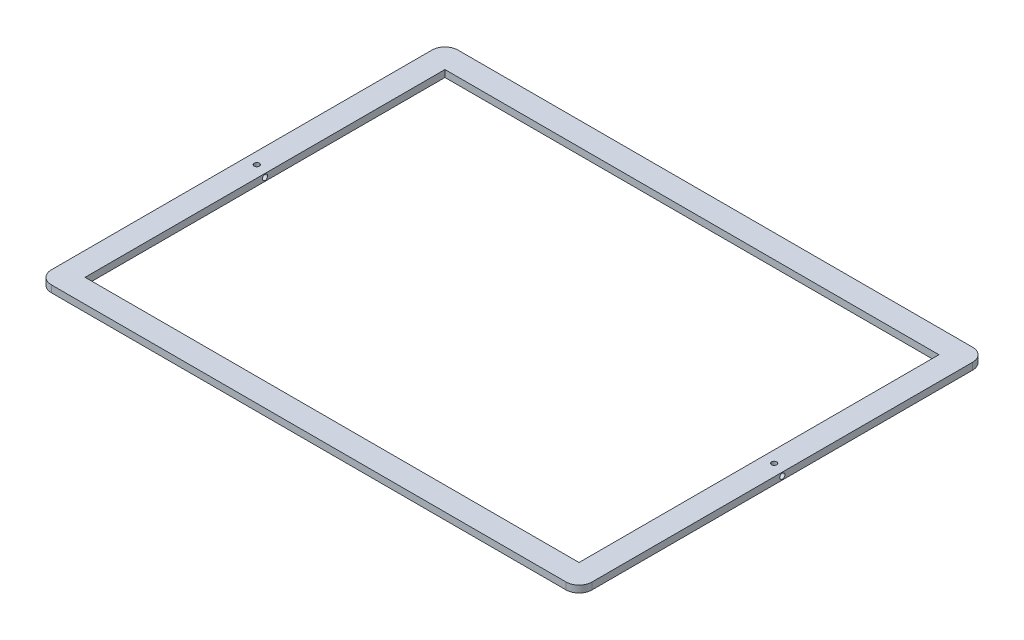
SolidWorks part; units mm, degrees
ref_plane "Спереди" through (0, 0, 0) normal (0, 0, 1) x (1, 0, 0)
ref_plane "Сверху" through (0, 0, 0) normal (0, 1, 0) x (1, 0, 0)
ref_plane "Справа" through (0, 0, 0) normal (1, 0, 0) x (0, 0, -1)
sketch "Эскиз1" plane through (0, 0, 0) normal (0, 1, 0) x (1, 0, 0)
  line L0 (0, 235) -> (0, -235) construction
  line L1 (-312.5, 235) -> (312.5, 235)
  line L2 (-312.5, 235) -> (-312.5, -235)
  line L3 (-312.5, -235) -> (312.5, -235)
  line L4 (312.5, 235) -> (312.5, -235)
  line L5 (-312.5, 0) -> (312.5, 0) construction
  line L6 (-285.5, 208) -> (285.5, 208)
  line L7 (285.5, 208) -> (285.5, -208)
  line L8 (-285.5, -208) -> (285.5, -208)
  line L9 (-285.5, 208) -> (-285.5, -208)
  dimension "D1" = 625
  dimension "D2" = 470
  dimension "D3" = 27
extrude "Бобышка-Вытянуть1" add sketch "Эскиз1" along normal mid plane 8
fillet "Скругление1" radius 15 4 edges at (312.5, 0, 235) (-312.5, 0, 235) (312.5, 0, -235) (-312.5, 0, -235)
ref_plane "Плоскость1" through (0, 0, -221.5) normal (0, 0, -1) x (-1, 0, 0)
ref_plane "Плоскость2" through (0, 0, 221.5) normal (0, 0, -1) x (-1, 0, 0)
ref_plane "Плоскость3" through (-299, 0, 0) normal (-1, 0, 0) x (0, 0, 1)
ref_plane "Плоскость4" through (299, 0, 0) normal (-1, 0, 0) x (0, 0, 1)
sketch "Эскиз3" plane through (0, 0, 0) normal (1, 0, 0) x (0, 0, -1)
  circle A0 centre (0, 0) radius 3
  dimension "D1" = 6
extrude "Вырез-Вытянуть2" cut sketch "Эскиз3" against normal through all and the other way through all
sketch "Эскиз4" plane through (0, 4, 0) normal (0, 1, 0) x (1, 0, 0)
  line L0 (-299, 4.4) -> (-299, -4.4) construction
  line L1 (299, 4.4) -> (299, -4.4) construction
  circle A0 centre (-299, 4) radius 3
  circle A1 centre (299, 4) radius 3
  dimension "D1" = 6
  dimension "D2" = 4
extrude "Вырез-Вытянуть3" cut sketch "Эскиз4" against normal through all
